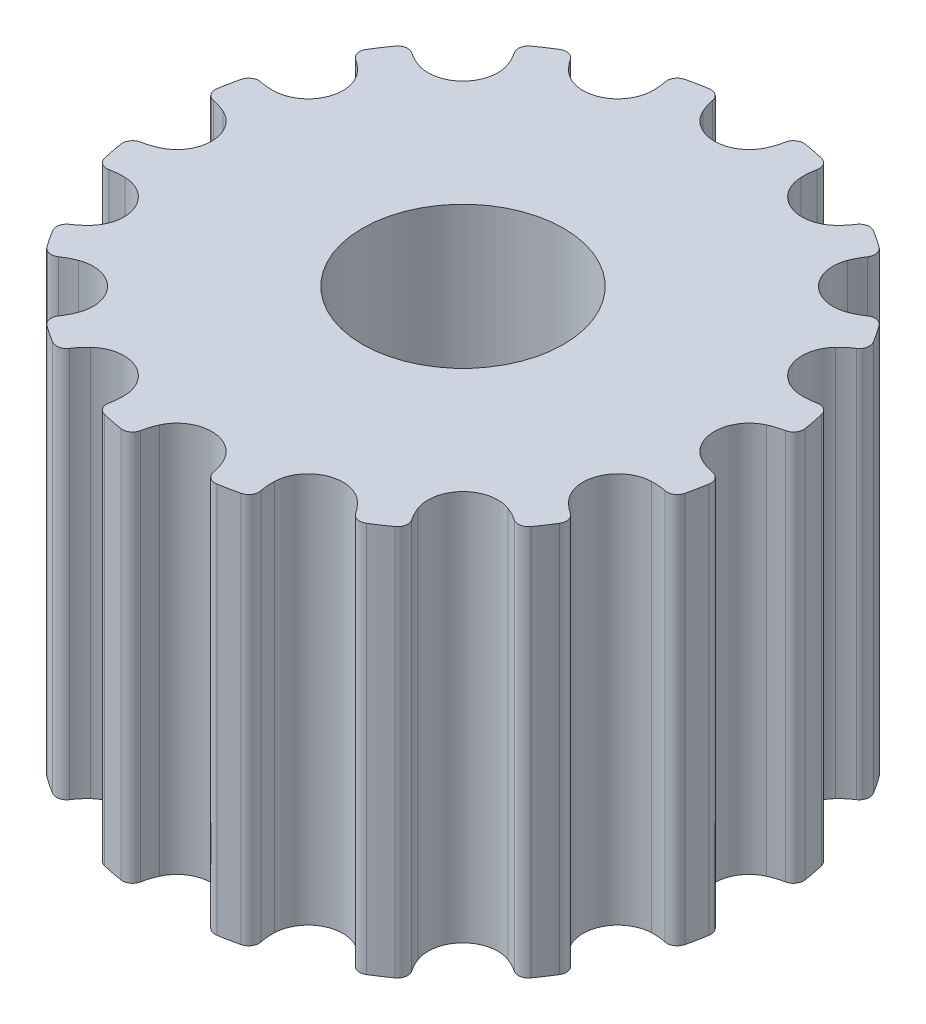
SolidWorks part; units mm, degrees
material "Alum Plate"
ref_plane "Front Plane" through (0, 0, 0) normal (0, 0, 1) x (1, 0, 0)
ref_plane "Top Plane" through (0, 0, 0) normal (0, 1, 0) x (1, 0, 0)
ref_plane "Right Plane" through (0, 0, 0) normal (1, 0, 0) x (0, 0, -1)
other "Bounding Box"
ref_plane "Default Plane" through (-8.9266, -12.7485, 0) normal (-0.1736, 0.9848, 0) x (0.9848, 0.1736, 0)
sketch "Sketch1" plane through (0, 0, 0) normal (0, 1, 0) x (1, 0, 0)
  line L0 (0, -7.8245) -> (0, 0) construction
  circle A0 centre (0, 0) radius 2.4511
  arc B0 (-1.8508, -6.777) -> (-1.6633, -7.0715) centre (-1.6061, -6.8282) ccw
  arc B1 (-1.6633, -7.0715) -> (-1.1695, -7.1697) centre (0, 0) ccw
  arc B2 (-1.1695, -7.1697) -> (-0.8836, -6.9694) centre (-1.1292, -6.923) ccw
  arc B3 (-0.7739, -6.6229) -> (-0.8836, -6.9694) centre (0.61, -7.2516) ccw
  arc B4 (0.7739, -6.6229) -> (-0.7739, -6.6229) centre (0, -6.9745) ccw
  arc B5 (0.8836, -6.9694) -> (0.7739, -6.6229) centre (-0.61, -7.2516) ccw
  arc B6 (0.8836, -6.9694) -> (1.1695, -7.1697) centre (1.1292, -6.923) ccw
  arc B7 (1.1695, -7.1697) -> (1.6633, -7.0715) centre (0, 0) ccw
  arc B8 (1.6633, -7.0715) -> (1.8508, -6.777) centre (1.6061, -6.8282) ccw
  arc B9 (1.8195, -6.4149) -> (1.8508, -6.777) centre (3.3386, -6.4662) ccw
  arc B10 (3.2495, -5.8226) -> (1.8195, -6.4149) centre (2.669, -6.4436) ccw
  arc B11 (3.4834, -6.1008) -> (3.2495, -5.8226) centre (2.2115, -6.9331) ccw
  arc B12 (3.4834, -6.1008) -> (3.8242, -6.1764) centre (3.6926, -5.9639) ccw
  arc B13 (3.8242, -6.1764) -> (4.2428, -5.8967) centre (0, 0) ccw
  arc B14 (4.2428, -5.8967) -> (4.3033, -5.5529) centre (4.0968, -5.6938) ccw
  arc B15 (4.1359, -5.2303) -> (4.3033, -5.5529) centre (5.559, -4.6963) ccw
  arc B16 (5.2303, -4.1359) -> (4.1359, -5.2303) centre (4.9317, -4.9317) ccw
  arc B17 (5.5529, -4.3033) -> (5.2303, -4.1359) centre (4.6963, -5.559) ccw
  arc B18 (5.5529, -4.3033) -> (5.8967, -4.2428) centre (5.6938, -4.0968) ccw
  arc B19 (5.8967, -4.2428) -> (6.1764, -3.8242) centre (0, 0) ccw
  arc B20 (6.1764, -3.8242) -> (6.1008, -3.4834) centre (5.9639, -3.6926) ccw
  arc B21 (5.8226, -3.2495) -> (6.1008, -3.4834) centre (6.9331, -2.2115) ccw
  arc B22 (6.4149, -1.8195) -> (5.8226, -3.2495) centre (6.4436, -2.669) ccw
  arc B23 (6.777, -1.8508) -> (6.4149, -1.8195) centre (6.4662, -3.3386) ccw
  arc B24 (6.777, -1.8508) -> (7.0715, -1.6633) centre (6.8282, -1.6061) ccw
  arc B25 (7.0715, -1.6633) -> (7.1697, -1.1695) centre (0, 0) ccw
  arc B26 (7.1697, -1.1695) -> (6.9694, -0.8836) centre (6.923, -1.1292) ccw
  arc B27 (6.6229, -0.7739) -> (6.9694, -0.8836) centre (7.2516, 0.61) ccw
  arc B28 (6.6229, 0.7739) -> (6.6229, -0.7739) centre (6.9745, 0) ccw
  arc B29 (6.9694, 0.8836) -> (6.6229, 0.7739) centre (7.2516, -0.61) ccw
  arc B30 (6.9694, 0.8836) -> (7.1697, 1.1695) centre (6.923, 1.1292) ccw
  arc B31 (7.1697, 1.1695) -> (7.0715, 1.6633) centre (0, 0) ccw
  arc B32 (7.0715, 1.6633) -> (6.777, 1.8508) centre (6.8282, 1.6061) ccw
  arc B33 (6.4149, 1.8195) -> (6.777, 1.8508) centre (6.4662, 3.3386) ccw
  arc B34 (5.8226, 3.2495) -> (6.4149, 1.8195) centre (6.4436, 2.669) ccw
  arc B35 (6.1008, 3.4834) -> (5.8226, 3.2495) centre (6.9331, 2.2115) ccw
  arc B36 (6.1008, 3.4834) -> (6.1764, 3.8242) centre (5.9639, 3.6926) ccw
  arc B37 (6.1764, 3.8242) -> (5.8967, 4.2428) centre (0, 0) ccw
  arc B38 (5.8967, 4.2428) -> (5.5529, 4.3033) centre (5.6938, 4.0968) ccw
  arc B39 (5.2303, 4.1359) -> (5.5529, 4.3033) centre (4.6963, 5.559) ccw
  arc B40 (4.1359, 5.2303) -> (5.2303, 4.1359) centre (4.9317, 4.9317) ccw
  arc B41 (4.3033, 5.5529) -> (4.1359, 5.2303) centre (5.559, 4.6963) ccw
  arc B42 (4.3033, 5.5529) -> (4.2428, 5.8967) centre (4.0968, 5.6938) ccw
  arc B43 (4.2428, 5.8967) -> (3.8242, 6.1764) centre (0, 0) ccw
  arc B44 (3.8242, 6.1764) -> (3.4834, 6.1008) centre (3.6926, 5.9639) ccw
  arc B45 (3.2495, 5.8226) -> (3.4834, 6.1008) centre (2.2115, 6.9331) ccw
  arc B46 (1.8195, 6.4149) -> (3.2495, 5.8226) centre (2.669, 6.4436) ccw
  arc B47 (1.8508, 6.777) -> (1.8195, 6.4149) centre (3.3386, 6.4662) ccw
  arc B48 (1.8508, 6.777) -> (1.6633, 7.0715) centre (1.6061, 6.8282) ccw
  arc B49 (1.6633, 7.0715) -> (1.1695, 7.1697) centre (0, 0) ccw
  arc B50 (1.1695, 7.1697) -> (0.8836, 6.9694) centre (1.1292, 6.923) ccw
  arc B51 (0.7739, 6.6229) -> (0.8836, 6.9694) centre (-0.61, 7.2516) ccw
  arc B52 (-0.7739, 6.6229) -> (0.7739, 6.6229) centre (0, 6.9745) ccw
  arc B53 (-0.8836, 6.9694) -> (-0.7739, 6.6229) centre (0.61, 7.2516) ccw
  arc B54 (-0.8836, 6.9694) -> (-1.1695, 7.1697) centre (-1.1292, 6.923) ccw
  arc B55 (-1.1695, 7.1697) -> (-1.6633, 7.0715) centre (0, 0) ccw
  arc B56 (-1.6633, 7.0715) -> (-1.8508, 6.777) centre (-1.6061, 6.8282) ccw
  arc B57 (-1.8195, 6.4149) -> (-1.8508, 6.777) centre (-3.3386, 6.4662) ccw
  arc B58 (-3.2495, 5.8226) -> (-1.8195, 6.4149) centre (-2.669, 6.4436) ccw
  arc B59 (-3.4834, 6.1008) -> (-3.2495, 5.8226) centre (-2.2115, 6.9331) ccw
  arc B60 (-3.4834, 6.1008) -> (-3.8242, 6.1764) centre (-3.6926, 5.9639) ccw
  arc B61 (-3.8242, 6.1764) -> (-4.2428, 5.8967) centre (0, 0) ccw
  arc B62 (-4.2428, 5.8967) -> (-4.3033, 5.5529) centre (-4.0968, 5.6938) ccw
  arc B63 (-4.1359, 5.2303) -> (-4.3033, 5.5529) centre (-5.559, 4.6963) ccw
  arc B64 (-5.2303, 4.1359) -> (-4.1359, 5.2303) centre (-4.9317, 4.9317) ccw
  arc B65 (-5.5529, 4.3033) -> (-5.2303, 4.1359) centre (-4.6963, 5.559) ccw
  arc B66 (-5.5529, 4.3033) -> (-5.8967, 4.2428) centre (-5.6938, 4.0968) ccw
  arc B67 (-5.8967, 4.2428) -> (-6.1764, 3.8242) centre (0, 0) ccw
  arc B68 (-6.1764, 3.8242) -> (-6.1008, 3.4834) centre (-5.9639, 3.6926) ccw
  arc B69 (-5.8226, 3.2495) -> (-6.1008, 3.4834) centre (-6.9331, 2.2115) ccw
  arc B70 (-6.4149, 1.8195) -> (-5.8226, 3.2495) centre (-6.4436, 2.669) ccw
  arc B71 (-6.777, 1.8508) -> (-6.4149, 1.8195) centre (-6.4662, 3.3386) ccw
  arc B72 (-6.777, 1.8508) -> (-7.0715, 1.6633) centre (-6.8282, 1.6061) ccw
  arc B73 (-7.0715, 1.6633) -> (-7.1697, 1.1695) centre (0, 0) ccw
  arc B74 (-7.1697, 1.1695) -> (-6.9694, 0.8836) centre (-6.923, 1.1292) ccw
  arc B75 (-6.6229, 0.7739) -> (-6.9694, 0.8836) centre (-7.2516, -0.61) ccw
  arc B76 (-6.6229, -0.7739) -> (-6.6229, 0.7739) centre (-6.9745, 0) ccw
  arc B77 (-6.9694, -0.8836) -> (-6.6229, -0.7739) centre (-7.2516, 0.61) ccw
  arc B78 (-6.9694, -0.8836) -> (-7.1697, -1.1695) centre (-6.923, -1.1292) ccw
  arc B79 (-7.1697, -1.1695) -> (-7.0715, -1.6633) centre (0, 0) ccw
  arc B80 (-7.0715, -1.6633) -> (-6.777, -1.8508) centre (-6.8282, -1.6061) ccw
  arc B81 (-6.4149, -1.8195) -> (-6.777, -1.8508) centre (-6.4662, -3.3386) ccw
  arc B82 (-5.8226, -3.2495) -> (-6.4149, -1.8195) centre (-6.4436, -2.669) ccw
  arc B83 (-6.1008, -3.4834) -> (-5.8226, -3.2495) centre (-6.9331, -2.2115) ccw
  arc B84 (-6.1008, -3.4834) -> (-6.1764, -3.8242) centre (-5.9639, -3.6926) ccw
  arc B85 (-6.1764, -3.8242) -> (-5.8967, -4.2428) centre (0, 0) ccw
  arc B86 (-5.8967, -4.2428) -> (-5.5529, -4.3033) centre (-5.6938, -4.0968) ccw
  arc B87 (-5.2303, -4.1359) -> (-5.5529, -4.3033) centre (-4.6963, -5.559) ccw
  arc B88 (-4.1359, -5.2303) -> (-5.2303, -4.1359) centre (-4.9317, -4.9317) ccw
  arc B89 (-4.3033, -5.5529) -> (-4.1359, -5.2303) centre (-5.559, -4.6963) ccw
  arc B90 (-4.3033, -5.5529) -> (-4.2428, -5.8967) centre (-4.0968, -5.6938) ccw
  arc B91 (-4.2428, -5.8967) -> (-3.8242, -6.1764) centre (0, 0) ccw
  arc B92 (-3.8242, -6.1764) -> (-3.4834, -6.1008) centre (-3.6926, -5.9639) ccw
  arc B93 (-3.2495, -5.8226) -> (-3.4834, -6.1008) centre (-2.2115, -6.9331) ccw
  arc B94 (-1.8195, -6.4149) -> (-3.2495, -5.8226) centre (-2.669, -6.4436) ccw
  arc B95 (-1.8508, -6.777) -> (-1.8195, -6.4149) centre (-3.3386, -6.4662) ccw
  dimension "D1" = 4.9022
sketch_block_instance "Block-GT2 16 Tooth Profile-1"
sketch_block "Block-GT2 16 Tooth Profile"
extrude "Boss-Extrude1" add sketch "Sketch1" along normal mid plane 9.525
